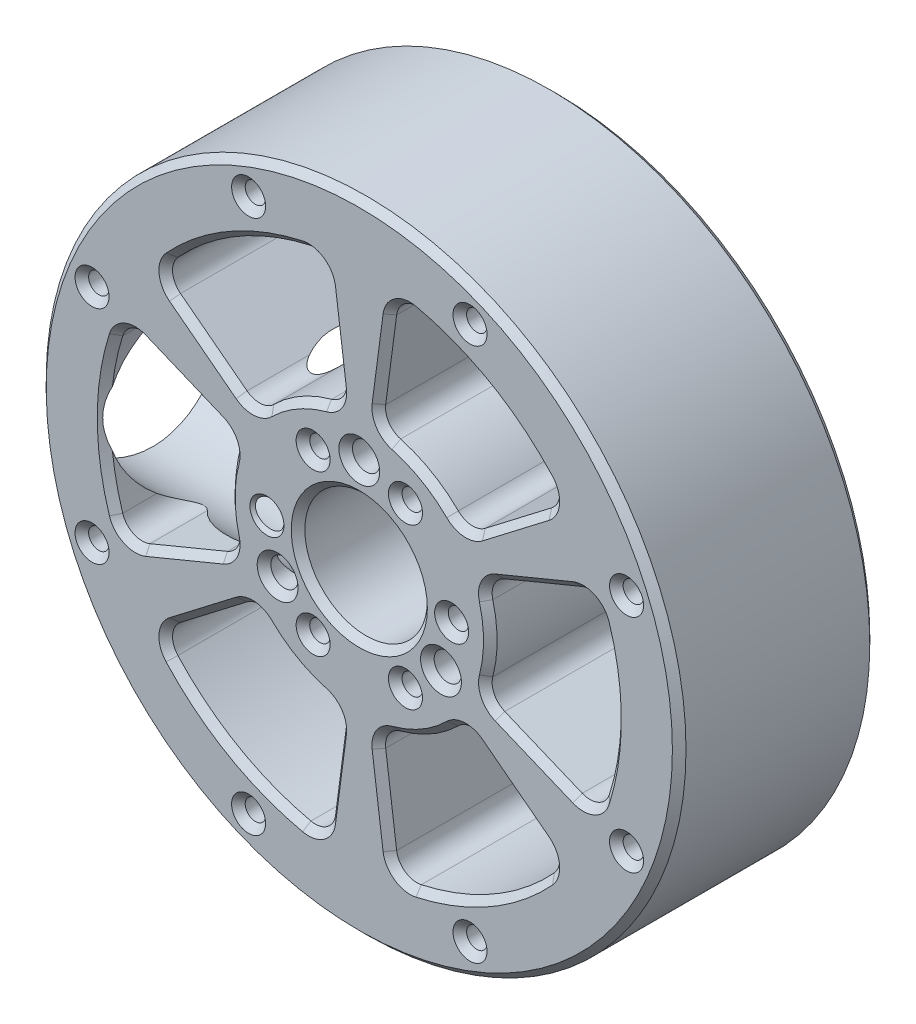
SolidWorks part; units mm, degrees
material "尼龙 101"
ref_plane "前视基准面" through (0, 0, 0) normal (0, 0, 1) x (1, 0, 0)
ref_plane "上视基准面" through (0, 0, 0) normal (0, 1, 0) x (1, 0, 0)
ref_plane "右视基准面" through (0, 0, 0) normal (1, 0, 0) x (0, 0, -1)
sketch "草图1" plane through (0, 0, 0) normal (0, 0, 1) x (1, 0, 0)
  line L0 (4.4861, 34.0753) -> (2.8777, 21.8582)
  line L1 (27.267, 20.9227) -> (17.4909, 13.4213)
  line L2 (31.7531, 13.1526) -> (20.3686, 8.437)
  line L3 (31.7531, -13.1526) -> (20.3686, -8.437)
  line L4 (27.267, -20.9227) -> (17.4909, -13.4213)
  line L5 (4.4861, -34.0753) -> (2.8777, -21.8582)
  line L6 (-4.4861, -34.0753) -> (-2.8777, -21.8582)
  line L7 (-27.267, -20.9227) -> (-17.4909, -13.4213)
  line L8 (-31.7531, -13.1526) -> (-20.3686, -8.437)
  line L9 (-31.7531, 13.1526) -> (-20.3686, 8.437)
  line L10 (-27.267, 20.9227) -> (-17.4909, 13.4213)
  line L11 (-4.4861, 34.0753) -> (-2.8777, 21.8582)
  line L12 (2.8777, 21.8582) -> (-2.8777, 21.8582) construction
  circle A0 centre (0, 0) radius 47
  arc A1 (29.9694, 22.5407) -> (34.477, 14.7508) centre (0, 0) ccw construction
  circle A3 centre (0, 0) radius 19.25 construction
  arc A5 (8.1092, 36.6127) -> (27.653, 25.3291) centre (0, 0) cw
  arc A7 (5.063, 18.5723) -> (13.5526, 13.6708) centre (0, 0) cw
  arc A9 (27.267, 20.9227) -> (27.653, 25.3291) centre (25.4407, 23.3028) ccw
  arc A11 (17.4909, 13.4213) -> (13.5526, 13.6708) centre (15.6646, 15.8013) cw
  arc A13 (2.8777, 21.8582) -> (5.063, 18.5723) centre (5.852, 21.4666) ccw
  arc A15 (4.4861, 34.0753) -> (8.1092, 36.6127) centre (7.4604, 33.6837) cw
  arc A17 (31.7531, 13.1526) -> (35.7621, 11.2836) centre (32.9012, 10.3809) cw
  circle A19 centre (16.264, 39.2649) radius 1.5
  circle A20 centre (16.264, 39.2649) radius 1.5
  circle A21 centre (-16.264, 39.2649) radius 1.5
  circle A22 centre (-16.264, 39.2649) radius 1.5
  circle A23 centre (-39.2649, 16.264) radius 1.5
  circle A24 centre (-39.2649, 16.264) radius 1.5
  circle A25 centre (-39.2649, -16.264) radius 1.5
  circle A26 centre (-39.2649, -16.264) radius 1.5
  circle A27 centre (-16.264, -39.2649) radius 1.5
  circle A28 centre (-16.264, -39.2649) radius 1.5
  circle A29 centre (16.264, -39.2649) radius 1.5
  circle A30 centre (16.264, -39.2649) radius 1.5
  circle A31 centre (39.2649, -16.264) radius 1.5
  circle A32 centre (39.2649, -16.264) radius 1.5
  circle A33 centre (39.2649, 16.264) radius 1.5
  circle A34 centre (39.2649, 16.264) radius 1.5
  circle A35 centre (0, 0) radius 9
  circle A36 centre (0, 0) radius 9
  circle A37 centre (6.7839, 11.75) radius 1.5
  circle A38 centre (6.7839, 11.75) radius 1.5
  circle A39 centre (-6.7839, 11.75) radius 1.5
  circle A40 centre (-6.7839, 11.75) radius 1.5
  circle A41 centre (-13.5677, 0) radius 1.5
  circle A42 centre (-13.5677, 0) radius 1.5
  circle A43 centre (-6.7839, -11.75) radius 1.5
  circle A44 centre (-6.7839, -11.75) radius 1.5
  circle A45 centre (6.7839, -11.75) radius 1.5
  circle A46 centre (6.7839, -11.75) radius 1.5
  circle A47 centre (13.5677, 0) radius 1.5
  circle A48 centre (13.5677, 0) radius 1.5
  circle A49 centre (0, 13.8564) radius 2
  circle A50 centre (0, 13.8564) radius 2
  circle A51 centre (12, -6.9282) radius 2
  circle A52 centre (12, -6.9282) radius 2
  circle A53 centre (-12, -6.9282) radius 2
  circle A54 centre (-12, -6.9282) radius 2
  arc A55 (35.7621, 11.2836) -> (35.7621, -11.2836) centre (0, 0) cw
  arc A57 (31.7531, -13.1526) -> (35.7621, -11.2836) centre (32.9012, -10.3809) ccw
  arc A59 (20.3686, -8.437) -> (18.6155, -4.9015) centre (21.5167, -5.6653) cw
  arc A61 (18.6155, 4.9015) -> (18.6155, -4.9015) centre (0, 0) cw
  arc A63 (20.3686, 8.437) -> (18.6155, 4.9015) centre (21.5167, 5.6653) ccw
  arc A65 (27.267, -20.9227) -> (27.653, -25.3291) centre (25.4407, -23.3028) cw
  arc A67 (27.653, -25.3291) -> (8.1092, -36.6127) centre (0, 0) cw
  arc A69 (4.4861, -34.0753) -> (8.1092, -36.6127) centre (7.4604, -33.6837) ccw
  arc A71 (2.8777, -21.8582) -> (5.063, -18.5723) centre (5.852, -21.4666) cw
  arc A72 (13.5526, -13.6708) -> (5.063, -18.5723) centre (0, 0) cw
  arc A73 (17.4909, -13.4213) -> (13.5526, -13.6708) centre (15.6646, -15.8013) ccw
  arc A74 (-4.4861, -34.0753) -> (-8.1092, -36.6127) centre (-7.4604, -33.6837) cw
  arc A75 (-8.1092, -36.6127) -> (-27.653, -25.3291) centre (0, 0) cw
  arc A76 (-27.267, -20.9227) -> (-27.653, -25.3291) centre (-25.4407, -23.3028) ccw
  arc A77 (-17.4909, -13.4213) -> (-13.5526, -13.6708) centre (-15.6646, -15.8013) cw
  arc A78 (-5.063, -18.5723) -> (-13.5526, -13.6708) centre (0, 0) cw
  arc A79 (-2.8777, -21.8582) -> (-5.063, -18.5723) centre (-5.852, -21.4666) ccw
  arc A80 (-31.7531, -13.1526) -> (-35.7621, -11.2836) centre (-32.9012, -10.3809) cw
  arc A81 (-35.7621, -11.2836) -> (-35.7621, 11.2836) centre (0, 0) cw
  arc A82 (-31.7531, 13.1526) -> (-35.7621, 11.2836) centre (-32.9012, 10.3809) ccw
  arc A83 (-20.3686, 8.437) -> (-18.6155, 4.9015) centre (-21.5167, 5.6653) cw
  arc A84 (-18.6155, -4.9015) -> (-18.6155, 4.9015) centre (0, 0) cw
  arc A85 (-20.3686, -8.437) -> (-18.6155, -4.9015) centre (-21.5167, -5.6653) ccw
  arc A86 (-27.267, 20.9227) -> (-27.653, 25.3291) centre (-25.4407, 23.3028) cw
  arc A87 (-27.653, 25.3291) -> (-8.1092, 36.6127) centre (0, 0) cw
  arc A88 (-4.4861, 34.0753) -> (-8.1092, 36.6127) centre (-7.4604, 33.6837) ccw
  arc A89 (-2.8777, 21.8582) -> (-5.063, 18.5723) centre (-5.852, 21.4666) cw
  arc A90 (-13.5526, 13.6708) -> (-5.063, 18.5723) centre (0, 0) cw
  arc A91 (-17.4909, 13.4213) -> (-13.5526, 13.6708) centre (-15.6646, 15.8013) ccw
  point P14 (29.7508, 22.8286)
  point P17 (15.2721, 11.7187)
  point P20 (2.5126, 19.0853)
  point P23 (4.8947, 37.1792)
  point P141 (0, 0)
  dimension "D3" = 94
  dimension "D4" = 3
  dimension "D5" = 45
  dimension "D6" = 6
  dimension "D10" = 0
  dimension "D11" = 0
  dimension "D12" = 0
  dimension "D13" = 0
  dimension "D14" = 0
  dimension "D15" = 0
  dimension "D16" = 0
  dimension "D17" = 0
  dimension "D18" = 0
  dimension "D19" = 0
  dimension "D20" = 0
  dimension "D21" = 0
  dimension "D22" = 0
  dimension "D23" = 0
  dimension "D24" = 0
  dimension "D25" = 0
  dimension "D26" = 0
  dimension "D27" = 0
extrude "凸台-拉伸1" add sketch "草图1" along normal blind 29
chamfer "倒角1" distance 1 angle 45 134 edges at (-3.6819, 27.9667, 0) (-3.354, 19.8053, 0) (-9.625, 16.671, 0) (-15.4749, 12.8073, 0) (-22.379, 17.172, 0) (-28.4293, 23.041, 0) (-18.75, 32.476, 0) (-5.7395, 36.141, 0) (-22.379, -17.172, 0) (-15.4749, -12.8073, 0) (-9.625, -16.671, 0) (-3.354, -19.8053, 0) (-3.6819, -27.9667, 0) (-5.7395, -36.141, 0) (-18.75, -32.476, 0) (-28.4293, -23.041, 0) (26.0609, -10.7948, 0) (18.8289, -6.998, 0) (19.25, 0, 0) (18.8289, 6.998, 0) (26.0609, 10.7948, 0) (34.1687, 13.1, 0) (37.5, 0, 0) (34.1687, -13.1, 0) (47, 0, 0) (22.379, 17.172, 0) (15.4749, 12.8073, 0) (9.625, 16.671, 0) (3.354, 19.8053, 0) (3.6819, 27.9667, 0) (5.7395, 36.141, 0) (18.75, 32.476, 0) (28.4293, 23.041, 0) (17.764, 39.2649, 0) (-14.764, 39.2649, 0) (-37.7649, 16.264, 0) (-37.7649, -16.264, 0) (-14.764, -39.2649, 0) (17.764, -39.2649, 0) (40.7649, -16.264, 0) (40.7649, 16.264, 0) (9, 0, 0) (8.2839, 11.75, 0) (-5.2839, 11.75, 0) (-12.0677, 0, 0) (-5.2839, -11.75, 0) (8.2839, -11.75, 0) (15.0677, 0, 0) (2, 13.8564, 0) (14, -6.9282, 0) (-10, -6.9282, 0) (3.6819, -27.9667, 0) (3.354, -19.8053, 0) (9.625, -16.671, 0) (15.4749, -12.8073, 0) (22.379, -17.172, 0) (28.4293, -23.041, 0) (18.75, -32.476, 0) (5.7395, -36.141, 0) (-26.0609, 10.7948, 0) (-18.8289, 6.998, 0) (-19.25, 0, 0) (-18.8289, -6.998, 0) (-26.0609, -10.7948, 0) (-34.1687, -13.1, 0) (-37.5, 0, 0) (-34.1687, 13.1, 0) (-28.4293, 23.041, 29) (-22.379, 17.172, 29) (-15.4749, 12.8073, 29) (-9.625, 16.671, 29) (-3.354, 19.8053, 29) (-3.6819, 27.9667, 29) (-5.7395, 36.141, 29) (-18.75, 32.476, 29) (-34.1687, -13.1, 29) (-26.0609, -10.7948, 29) (-18.8289, -6.998, 29) (-19.25, 0, 29) (-18.8289, 6.998, 29) (-26.0609, 10.7948, 29) (-34.1687, 13.1, 29) (-37.5, 0, 29) (-5.7395, -36.141, 29) (-3.6819, -27.9667, 29) (-3.354, -19.8053, 29) (-9.625, -16.671, 29) (-15.4749, -12.8073, 29) (-22.379, -17.172, 29) (-28.4293, -23.041, 29) (-18.75, -32.476, 29) (28.4293, -23.041, 29) (22.379, -17.172, 29) (15.4749, -12.8073, 29) (9.625, -16.671, 29) (3.354, -19.8053, 29) (3.6819, -27.9667, 29) (5.7395, -36.141, 29) (18.75, -32.476, 29) (34.1687, 13.1, 29) (26.0609, 10.7948, 29) (18.8289, 6.998, 29) (19.25, 0, 29) (18.8289, -6.998, 29) (26.0609, -10.7948, 29) (34.1687, -13.1, 29) (37.5, 0, 29) (-10, -6.9282, 29) (2, 13.8564, 29) (8.2839, -11.75, 29) (-12.0677, 0, 29) (8.2839, 11.75, 29) (40.7649, 16.264, 29) (17.764, -39.2649, 29) (-37.7649, -16.264, 29) (-14.764, 39.2649, 29) (5.7395, 36.141, 29) (3.6819, 27.9667, 29) (3.354, 19.8053, 29) (9.625, 16.671, 29) (15.4749, 12.8073, 29) (22.379, 17.172, 29) (28.4293, 23.041, 29) (18.75, 32.476, 29) (47, 0, 29) (17.764, 39.2649, 29) (-37.7649, 16.264, 29) (-14.764, -39.2649, 29) (40.7649, -16.264, 29) (9, 0, 29) (-5.2839, 11.75, 29) (-5.2839, -11.75, 29) (15.0677, 0, 29) (14, -6.9282, 29)
sketch "草图2" plane through (-64.2649, 0, 0) normal (1, 0, 0) x (0, 0, -1)
  circle A0 centre (-14.5, 0) radius 14.1
  dimension "D1" = 28.2
  dimension "D2" = 14.5
extrude "切除-拉伸1" cut sketch "草图2" along normal blind 54
